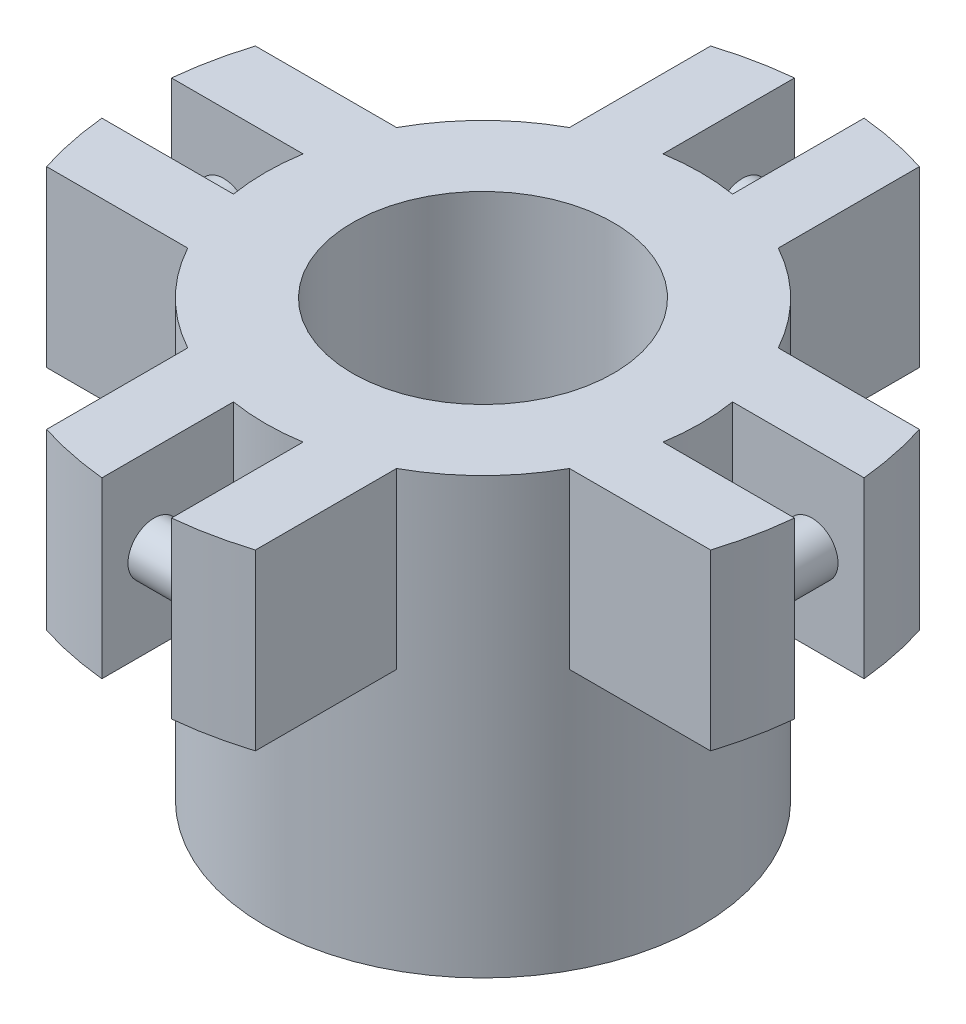
SolidWorks part; units mm, degrees
ref_plane "Front Plane" through (0, 0, 0) normal (0, 0, 1) x (1, 0, 0)
ref_plane "Top Plane" through (0, 0, 0) normal (0, 1, 0) x (1, 0, 0)
ref_plane "Right Plane" through (0, 0, 0) normal (1, 0, 0) x (0, 0, -1)
sketch "Sketch1" plane through (0, 0, 0) normal (0, 1, 0) x (1, 0, 0)
  circle A0 centre (0, 0) radius 7.5
  circle A1 centre (0, 0) radius 12.5
  dimension "D1" = 15
  dimension "D2" = 25
extrude "Boss-Extrude1" add sketch "Sketch1" along normal blind 20
sketch "Sketch2" plane through (0, 20, 0) normal (0, 1, 0) x (1, 0, 0)
  line L0 (-20, 0) -> (20, 0) construction
  line L1 (0, 20) -> (0, -20) construction
  line L2 (-2, 19.8997) -> (-2, 12.339)
  line L3 (-19.8997, -2) -> (-12.339, -2)
  line L4 (2, 19.8997) -> (2, 12.339)
  line L5 (-19.8997, 2) -> (-12.339, 2)
  line L6 (-6, 19.0788) -> (-6, 10.9659)
  line L7 (6, 19.0788) -> (6, 10.9659)
  line L8 (-19.0788, 6) -> (-10.9659, 6)
  line L9 (-19.0788, -6) -> (-10.9659, -6)
  line L10 (6, 27.3662) -> (6, -26.3963) construction
  line L11 (2, 27.3662) -> (2, -26.3963) construction
  line L12 (0, 27.3662) -> (0, -26.3963) construction
  line L13 (-2, 27.3662) -> (-2, -26.3963) construction
  line L14 (-6, 27.3662) -> (-6, -26.3963) construction
  line L15 (-27.3277, 6) -> (41.3765, 6) construction
  line L16 (-27.3277, 2) -> (41.3765, 2) construction
  line L17 (-27.3277, 0) -> (41.3765, 0) construction
  line L18 (-27.3277, -2) -> (41.3765, -2) construction
  line L19 (-27.3277, -6) -> (41.3765, -6) construction
  line L25 (10.9659, 6) -> (19.0788, 6)
  line L26 (12.339, 2) -> (19.8997, 2)
  line L27 (12.339, -2) -> (19.8997, -2)
  line L28 (10.9659, -6) -> (19.0788, -6)
  line L29 (6, -10.9659) -> (6, -19.0788)
  line L30 (2, -12.339) -> (2, -19.8997)
  line L31 (-2, -12.339) -> (-2, -19.8997)
  line L32 (-6, -10.9659) -> (-6, -19.0788)
  arc A0 (-19.0788, 6) -> (-19.8997, 2) centre (0, 0) ccw
  circle A1 centre (0, 0) radius 7.5 construction
  circle A2 centre (0, 0) radius 12.5 construction
  circle A3 centre (0, 0) radius 7.5
  arc A4 (-12.339, 2) -> (-12.339, -2) centre (0, 0) ccw
  arc A5 (6, 19.0788) -> (2, 19.8997) centre (0, 0) ccw
  arc A6 (19.0788, -6) -> (19.8997, -2) centre (0, 0) ccw
  arc A7 (-6, -19.0788) -> (-2, -19.8997) centre (0, 0) ccw
  arc A8 (-2, 19.8997) -> (-6, 19.0788) centre (0, 0) ccw
  arc A9 (19.8997, 2) -> (19.0788, 6) centre (0, 0) ccw
  arc A10 (2, -19.8997) -> (6, -19.0788) centre (0, 0) ccw
  arc A11 (-19.8997, -2) -> (-19.0788, -6) centre (0, 0) ccw
  arc A12 (-6, 10.9659) -> (-10.9659, 6) centre (0, 0) ccw
  arc A13 (2, 12.339) -> (-2, 12.339) centre (0, 0) ccw
  arc A14 (-10.9659, -6) -> (-6, -10.9659) centre (0, 0) ccw
  arc A15 (-2, -12.339) -> (2, -12.339) centre (0, 0) ccw
  arc A16 (6, -10.9659) -> (10.9659, -6) centre (0, 0) ccw
  arc A17 (12.339, -2) -> (12.339, 2) centre (0, 0) ccw
  arc A18 (10.9659, 6) -> (6, 10.9659) centre (0, 0) ccw
  dimension "D1" = 40
  dimension "D2" = 2
  dimension "D3" = 2
  dimension "D4" = 4
  dimension "D5" = 4
  dimension "D6" = 4
  dimension "D7" = 4
extrude "Boss-Extrude2" add sketch "Sketch2" along normal mid plane 10
sketch "Sketch3" plane through (0, 0, -2) normal (0, 0, 1) x (1, 0, 0)
  line L0 (-19.8997, 25) -> (-19.8997, 15) construction
  line L1 (-19.0788, 25) -> (-10.9659, 25) construction
  circle A0 centre (-16.8997, 20) radius 1.5
  dimension "D1" = 3
  dimension "D3" = 5
  dimension "D2" = 3
extrude "Boss-Extrude3" add sketch "Sketch3" along normal blind 7
pattern_circular "CirPattern1" count 4 over 360 of "Boss-Extrude3"
